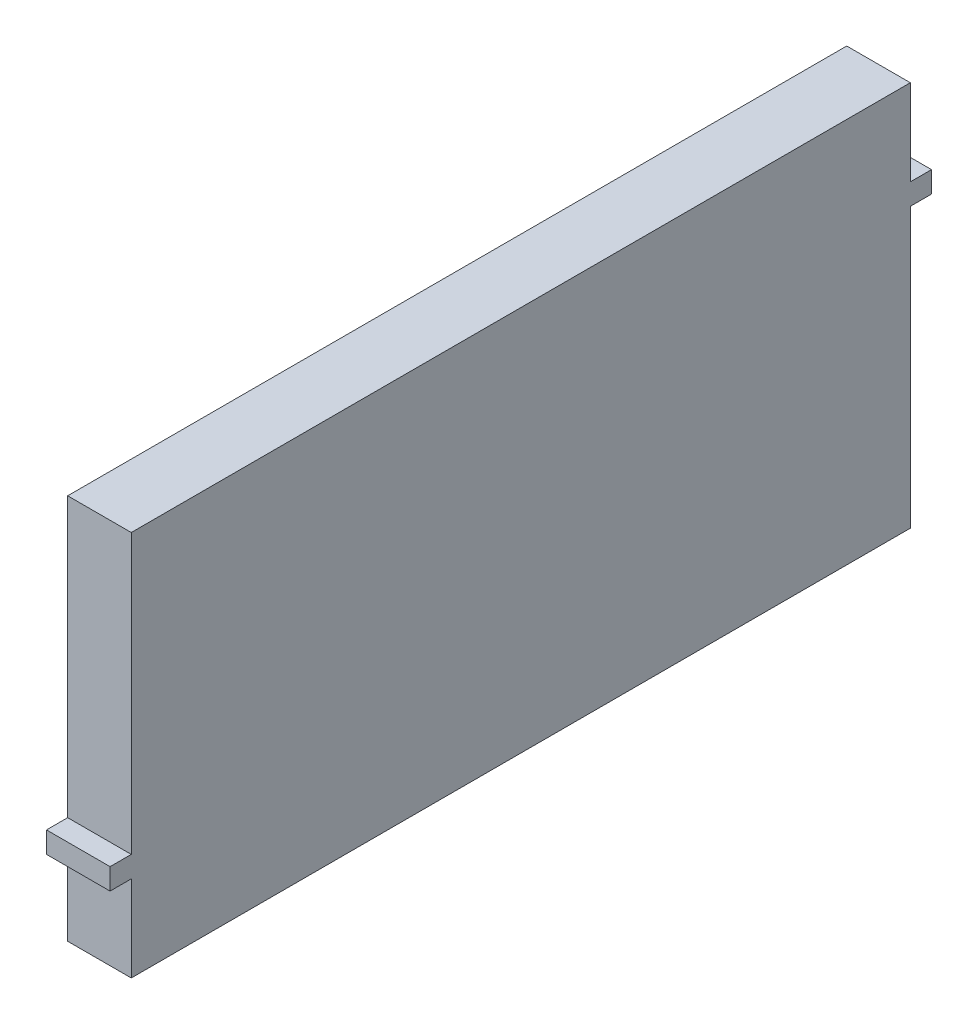
SolidWorks part; units mm, degrees
material "Balsa"
ref_plane "Front Plane" through (0, 0, 0) normal (0, 0, 1) x (1, 0, 0)
ref_plane "Top Plane" through (0, 0, 0) normal (0, 1, 0) x (1, 0, 0)
ref_plane "Right Plane" through (0, 0, 0) normal (1, 0, 0) x (0, 0, -1)
sketch "Sketch1" plane through (243.0177, 0, 0) normal (1, 0, 0) x (0, 0, -1)
  line L0 (-679.2499, 377.7667) -> (-682.4249, 377.7667) construction
  line L1 (-682.4249, 377.7667) -> (-682.4249, 374.5917) construction
  line L2 (-682.4249, 374.5917) -> (-679.2499, 374.5917) construction
  line L3 (-562.5687, 419.518) -> (-559.3937, 419.518) construction
  line L4 (-559.3937, 406.6592) -> (-562.5687, 406.6592) construction
  line L5 (-562.5687, 419.518) -> (-559.3937, 419.518) construction
  line L6 (-562.5687, 403.4842) -> (-559.3937, 403.4842) construction
  line L7 (-559.3937, 403.4842) -> (-559.3937, 406.6592) construction
  line L8 (-682.4249, 419.518) -> (-679.2499, 419.518) construction
  line L9 (-562.5687, 361.733) -> (-559.3937, 361.733) construction
  line L10 (-562.5687, 361.733) -> (-559.3937, 361.733) construction
  line L11 (-682.4249, 419.518) -> (-679.2499, 419.518) construction
  line L12 (-679.2499, 377.7667) -> (-682.4249, 377.7667)
  line L13 (-682.4249, 377.7667) -> (-682.4249, 374.5917)
  line L14 (-682.4249, 374.5917) -> (-679.2499, 374.5917)
  line L16 (-559.3937, 406.6592) -> (-562.5687, 406.6592)
  line L18 (-562.5687, 403.4842) -> (-559.3937, 403.4842)
  line L19 (-559.3937, 403.4842) -> (-559.3937, 406.6592)
  line L21 (-679.2499, 419.518) -> (-562.5687, 419.518)
  line L22 (-682.4249, 361.733) -> (-679.2499, 361.733) construction
  line L23 (-682.4249, 361.733) -> (-679.2499, 361.733) construction
  line L25 (-562.5687, 406.6592) -> (-562.5687, 419.518)
  line L26 (-562.5687, 403.4842) -> (-562.5687, 361.733)
  line L28 (-679.2499, 361.733) -> (-679.2499, 374.5917)
  line L29 (-679.2499, 419.518) -> (-679.2499, 377.7667)
  line L30 (-562.5687, 361.733) -> (-679.2499, 361.733)
extrude "Boss-Extrude1" add sketch "Sketch1" along normal up to surface (9.525 mm away)
